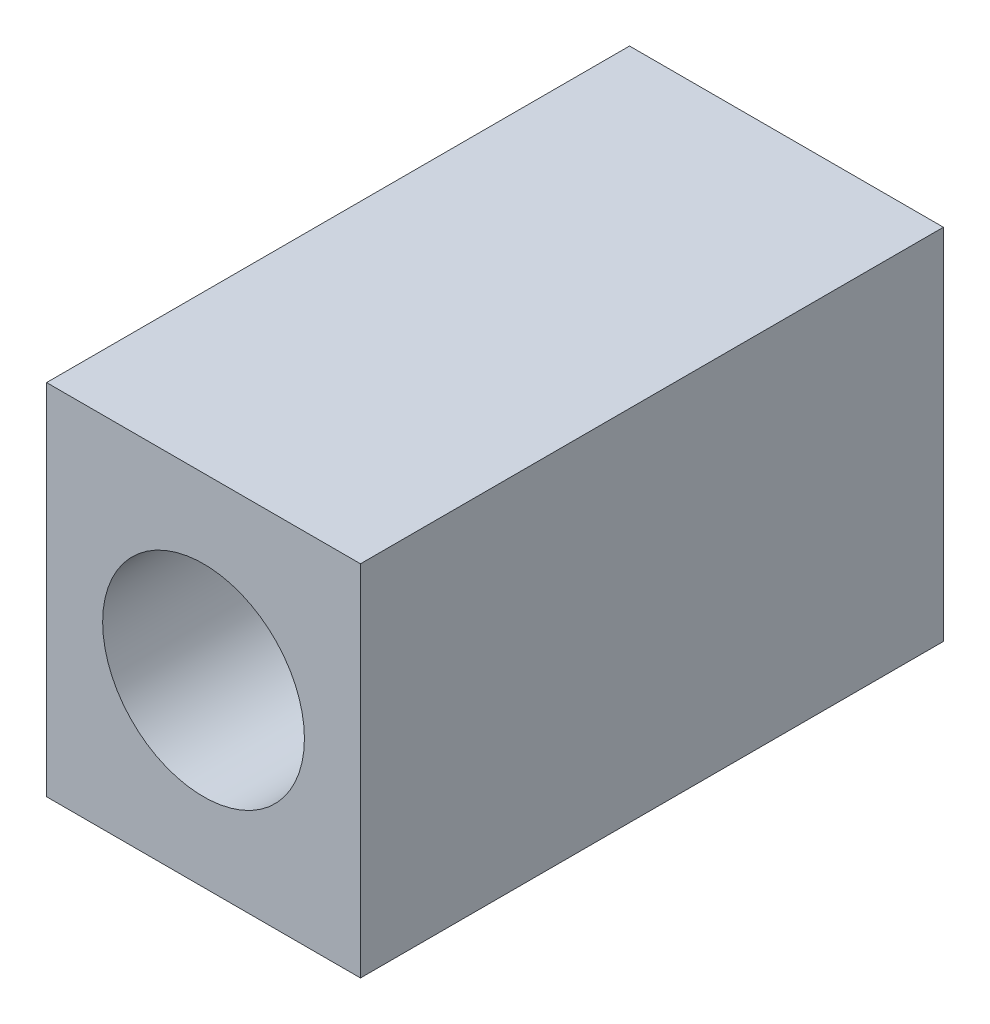
SolidWorks part; units mm, degrees
ref_plane "Plan de face" through (0, 0, 0) normal (0, 0, 1) x (1, 0, 0)
ref_plane "Plan de dessus" through (0, 0, 0) normal (0, 1, 0) x (1, 0, 0)
ref_plane "Plan de droite" through (0, 0, 0) normal (1, 0, 0) x (0, 0, -1)
sketch "Esquisse1" plane through (0, 0, 0) normal (0, 0, 1) x (1, 0, 0)
  line L1 (-3.5, -4) -> (3.5, -4)
  line L2 (-3.5, -4) -> (-3.5, 4)
  line L3 (-3.5, 4) -> (3.5, 4)
  line L4 (3.5, -4) -> (3.5, 4)
  line L5 (-3.5, -4) -> (3.5, 4) construction
  line L6 (-3.5, 4) -> (3.5, -4) construction
  circle A0 centre (0, 0) radius 2.25
  point P0 (0, 0)
  dimension "D3" = 4.5
  dimension "D1" = 7
  dimension "D2" = 8
extrude "Boss.-Extru.1" add sketch "Esquisse1" along normal blind 13
sketch "Esquisse2" plane through (0, -4, 0) normal (0, -1, 0) x (1, 0, 0)
  line L0 (-3.5, 8) -> (3.5, 0) construction
  line L1 (3.5, 0) -> (3.5, 4) construction
  line L3 (3.5, 4) -> (0, 4) construction
  line L4 (-3.5, 13) -> (-3.5, 0) construction
  circle A0 centre (0, 4) radius 1.75
  point P5 (-3.5, 5.9735)
  point P7 (-3.5, 13)
  point P10 (0, 0)
  point P11 (-4.8498, 13)
  point P12 (3.5, 6.5)
  point P13 (0, 0)
  dimension "D1" = 3.5
  dimension "D2" = 8
extrude "Enlèv. mat.-Extru.1" cut sketch "Esquisse2" against normal blind 1
